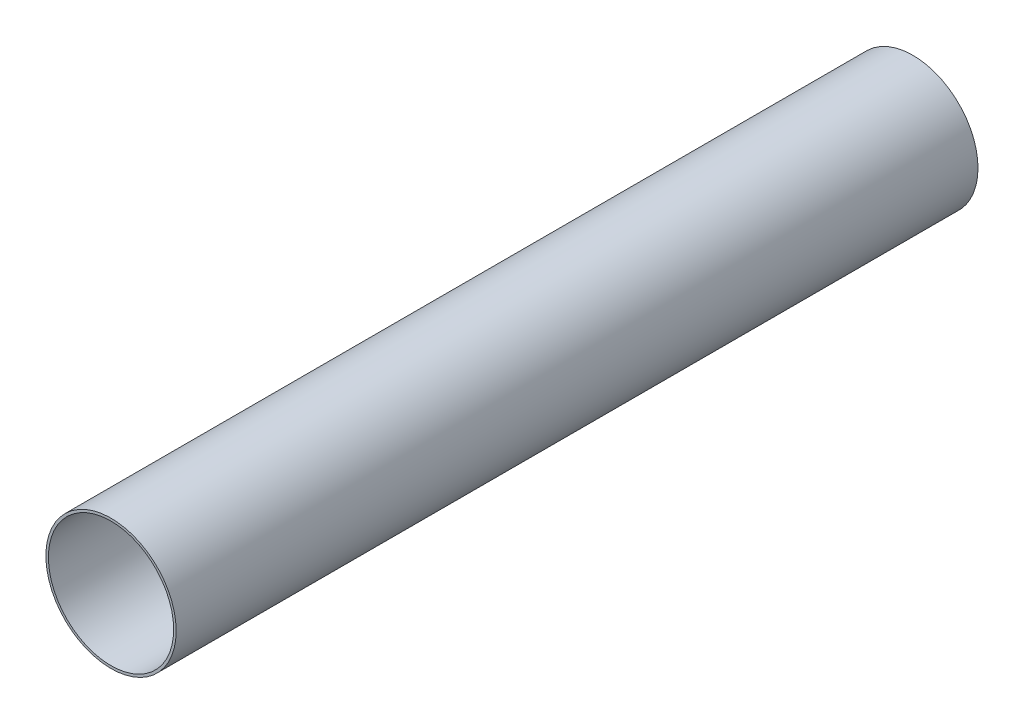
SolidWorks part; units mm, degrees
ref_plane "Front" through (0, 0, 0) normal (0, 0, 1) x (1, 0, 0)
ref_plane "Top" through (0, 0, 0) normal (0, 1, 0) x (1, 0, 0)
ref_plane "Right" through (0, 0, 0) normal (1, 0, 0) x (0, 0, -1)
sketch "Sketch2" plane through (0, 0, 0) normal (0, 0, 1) x (1, 0, 0)
  circle A0 centre (0, 0) radius 12.5
  circle A1 centre (0, 0) radius 13
  dimension "D2" = 25
  dimension "D1" = 0.5
extrude "Boss-Extrude1" add sketch "Sketch2" along normal blind 160
